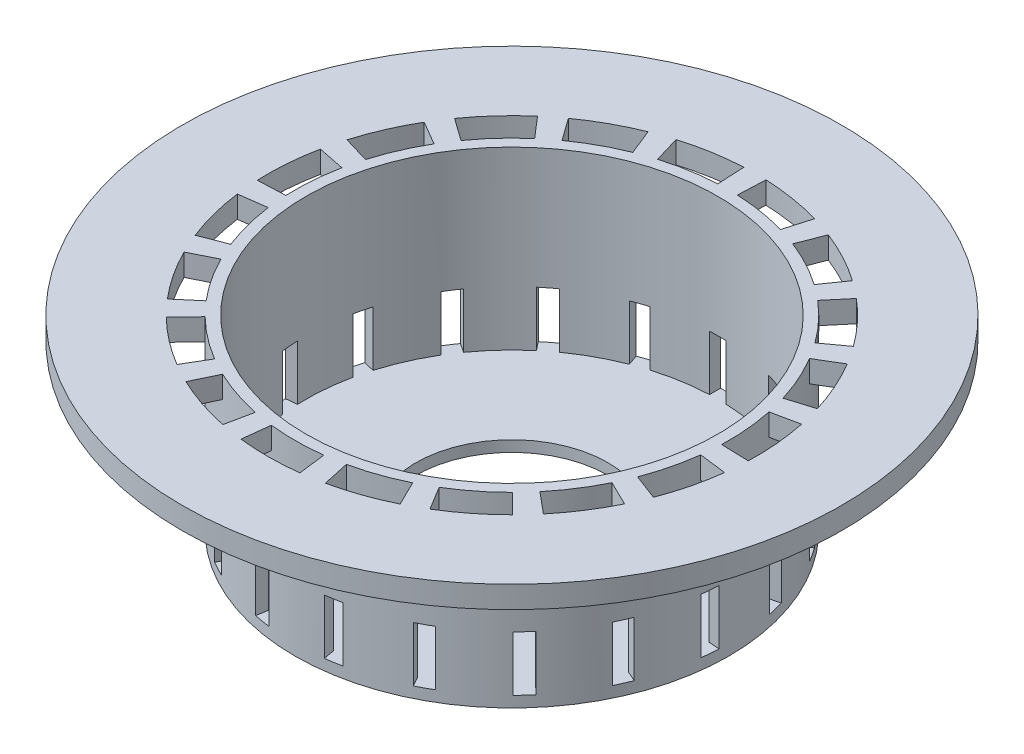
SolidWorks part; units mm, degrees
ref_plane "Front Plane" through (0, 0, 0) normal (0, 0, 1) x (1, 0, 0)
ref_plane "Top Plane" through (0, 0, 0) normal (0, 1, 0) x (1, 0, 0)
ref_plane "Right Plane" through (0, 0, 0) normal (1, 0, 0) x (0, 0, -1)
sketch "Sketch1" plane through (0, 0, 0) normal (0, 1, 0) x (1, 0, 0)
  circle A0 centre (0, 0) radius 19.75
  circle A1 centre (0, 0) radius 18.75
  dimension "D1" = 39.5
  dimension "D2" = 1
extrude "Boss-Extrude1" add sketch "Sketch1" along normal blind 16
sketch "Sketch2" plane through (0, 0, 0) normal (0, 1, 0) x (1, 0, 0)
  line L0 (0, 19.75) -> (0, 0) construction
  line L1 (9.5299, 17.6098) -> (3.2957, 19.75)
  line L2 (3.2957, 19.75) -> (-3.2957, 19.75)
  line L3 (-3.2957, 19.75) -> (-9.5299, 17.6098)
  line L4 (-9.5299, 17.6098) -> (-14.7315, 13.5613)
  line L5 (-14.7315, 13.5613) -> (-18.3366, 8.0432)
  line L6 (-18.3366, 8.0432) -> (-19.9547, 1.6535)
  line L7 (-19.9547, 1.6535) -> (-19.4104, -4.9154)
  line L8 (-19.4104, -4.9154) -> (-16.7627, -10.9516)
  line L9 (-16.7627, -10.9516) -> (-12.2984, -15.801)
  line L10 (-12.2984, -15.801) -> (-6.5015, -18.9382)
  line L11 (-6.5015, -18.9382) -> (0, -20.0231)
  line L12 (0, -20.0231) -> (6.5015, -18.9382)
  line L13 (6.5015, -18.9382) -> (12.2984, -15.801)
  line L14 (12.2984, -15.801) -> (16.7627, -10.9516)
  line L15 (16.7627, -10.9516) -> (19.4104, -4.9154)
  line L16 (19.4104, -4.9154) -> (19.9547, 1.6535)
  line L17 (19.9547, 1.6535) -> (18.3366, 8.0432)
  line L18 (18.3366, 8.0432) -> (14.7315, 13.5613)
  line L19 (14.7315, 13.5613) -> (9.5299, 17.6098)
  line L20 (-0.7498, 19.7358) -> (-0.7498, 18.735)
  line L21 (0.7498, 19.7358) -> (0.7498, 18.735)
  circle A0 centre (0, 0) radius 19.75 construction
  circle A1 centre (0, 0) radius 19.75 construction
  arc A2 (-0.7498, 18.735) -> (0.7498, 18.735) centre (0, 0) cw
  circle A3 centre (0, 0) radius 18.75 construction
  arc A4 (-0.7498, 19.7358) -> (0.7498, 19.7358) centre (0, 0) cw
  point P1 (0, 19.75)
  point P32 (0, 18.75)
  dimension "D1" = 1.5
extrude "Cut-Extrude1" cut sketch "Sketch2" along normal blind 5 contours A4 L20 A2 L21
sketch "Sketch3" plane through (0, 0, 0) normal (0, 0, 1) x (1, 0, 0)
  line L0 (0, 0) -> (0, 16) construction
  line L1 (18.75, 16) -> (-18.75, 16) construction
pattern_circular "CirPattern1" count 19 over 360 about axis through (0, 0, 0) along (0, 1, 0) of "Cut-Extrude1"
sketch "Sketch4" plane through (0, 16, 0) normal (0, 1, 0) x (1, 0, 0)
  line L0 (0.8898, 22.2322) -> (0.7498, 18.735)
  line L1 (-1.1095, 22.2223) -> (-0.935, 18.7267)
  arc A1 (0.8898, 22.2322) -> (-1.1095, 22.2223) centre (0, 0) ccw
  circle A2 centre (0, 0) radius 18.75 construction
  arc A3 (-0.935, 18.7267) -> (0.7498, 18.735) centre (0, 0) cw
  circle A4 centre (0, 0) radius 19.75 construction
  dimension "D1" = 2.5
  dimension "D2" = 2
extrude "Boss-Extrude2" add sketch "Sketch4" against normal blind 2
pattern_circular "CirPattern2" count 19 over 360 about axis through (0, 0, 0) along (0, 1, 0) of "Boss-Extrude2"
sketch "Sketch5" plane through (0, 0, 0) normal (0, -1, 0) x (1, 0, 0)
  circle A0 centre (0, 0) radius 19.75
  arc A1 (8.7338, 17.7139) -> (3.988, 19.3432) centre (0, 0) ccw construction
  circle A2 centre (0, 0) radius 8.75
  dimension "D1" = 17.5
extrude "Boss-Extrude3" add sketch "Sketch5" along normal blind 1
sketch "Sketch6" plane through (0, 16, 0) normal (0, 1, 0) x (1, 0, 0)
  circle A0 centre (0, 0) radius 22.25
  arc A1 (8.0603, 20.7387) -> (6.1662, 21.3785) centre (0, 0) ccw construction
  circle A2 centre (0, 0) radius 30
  dimension "D1" = 60
extrude "Boss-Extrude4" add sketch "Sketch6" against normal up to surface (2 mm away) up to face at (-9.8985, 14, 18.5088)
equation "\"diameter_ring_outer\" = 60mm"
equation "\"height_ring\"= 15mm"
equation "\"dist_tube_bottom\"= 1mm"
equation "\"diameter_ring_inner\" = 40mm"
equation "\"length_spring_expand\"= 15mm"
equation "\"length_spring_compress\"= 7.5mm"
equation "\"height_slit\"= 5mm"
equation "\"diameter_spring_inner\"= 3.5mm"
equation "\"length_slit_inner\"= 1.5mm"
equation "\"num_electrodes\"= 19"
equation "\"diameter_screw_Cz\"= 13mm"
equation "\"dist_spring_center\"= 7mm"
equation "\"height_thread\"= 2mm"
equation "\"width_wall\"= 1mm"
equation "\"diameter_tube\"= 2mm"
equation "\"length_stop\" = 2mm"
equation "\"width_stop\"= 1mm"
equation "\"height_stop\"= 2mm"
equation "\"D1@Sketch1\"=\"diameter_ring_inner\"-\"offset\""
equation "\"offset\"= 0.5mm"
equation "\"D2@Sketch1\"=\"width_wall\""
equation "\"D1@Boss-Extrude1\"=\"height_ring\"-\"width_wall\"+\"height_stop\""
equation "\"D1@Sketch2\"=\"length_slit_inner\""
equation "\"D1@Cut-Extrude1\"=\"height_slit\""
equation "\"D1@CirPattern1\"=\"num_electrodes\""
equation "\"D1@Sketch4\"=\"width_wall\"*2+\"offset\""
equation "\"D2@Sketch4\"=\"length_stop\""
equation "\"D1@Boss-Extrude2\"=\"height_stop\""
equation "\"D1@CirPattern2\"=\"num_electrodes\""
equation "\"D1@Boss-Extrude3\"=\"width_wall\""
equation "\"D1@Sketch6\"=\"diameter_ring_outer\""
equation "\"D1@Sketch5\"=\"diameter_screw_Cz\"+\"width_wall\"*4+\"offset\""
equation "\"indent_thread\"= 1mm"
equation "\"D1@Sketch1\"=\"diameter_ring_outer\""
equation "\"diameter_screw_Cz_top\"= 1mm"
